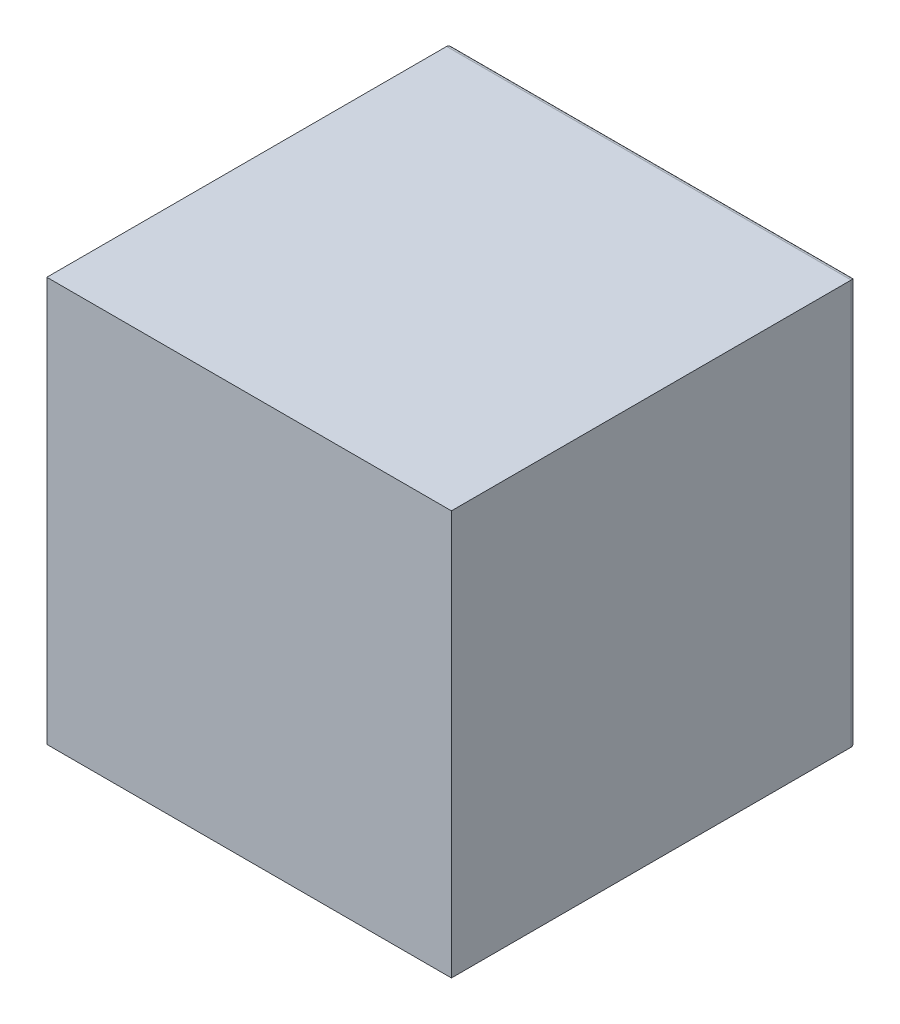
SolidWorks part; units mm, degrees
material "Stainless Steel (ferritic)"
ref_plane "Front Plane" through (0, 0, 0) normal (0, 0, 1) x (1, 0, 0)
ref_plane "Top Plane" through (0, 0, 0) normal (0, 1, 0) x (1, 0, 0)
ref_plane "Right Plane" through (0, 0, 0) normal (1, 0, 0) x (0, 0, -1)
sketch "Sketch2" plane through (0, 0, 0) normal (0, 1, 0) x (1, 0, 0)
  line L0 (250, -1250) -> (50250, -1250) construction
  line L1 (0, 0) -> (2500, 0)
  line L2 (0, 0) -> (0, -2500)
  line L3 (0, -2500) -> (2500, -2500)
  line L4 (2500, 0) -> (2500, -2500)
  line L5 (0, 0) -> (2500, -2500) construction
  line L6 (0, -2500) -> (2500, 0) construction
  line L7 (1250, -2250) -> (1250, 47750) construction
  point P4 (1250, -1250)
  dimension "D1" = 2500
  dimension "2500" = 2500
extrude "Boss-Extrude1" add sketch "Sketch2" along normal blind 2500
sketch "Sketch6" plane through (0, 0, 0) normal (0, 0, 1) x (1, 0, 0)
  line L0 (0, 250) -> (0, 50250) construction
  line L1 (0, 2500) -> (0, 0) construction
  line L2 (2500, 250) -> (2500, 50250) construction
  line L3 (2500, 2500) -> (2500, 0) construction
  line L4 (1500, 1250) -> (51500, 1250) construction
  line L6 (474.6639, 2000) -> (1974.6639, 2000)
  line L7 (474.6639, 2000) -> (474.6639, 500)
  line L8 (474.6639, 500) -> (1974.6639, 500)
  line L9 (1974.6639, 2000) -> (1974.6639, 500)
  line L10 (1224.6639, 500) -> (1224.6639, 2000) construction
  line L11 (474.6639, 1250) -> (1974.6639, 1250) construction
  point P5 (0, 1250)
  point P10 (2500, 1250)
  point P11 (1224.6639, 1250)
  dimension "D1" = 1500
  dimension "D2" = 1500
sketch "Sketch8" plane through (0, 0, 0) normal (0, 0, 1) x (1, 0, 0)
extrude "Cut-Extrude9" cut sketch "Sketch6" along normal blind 500
sketch "Sketch13" plane through (0, 0, 0) normal (0, 0, 1) x (1, 0, 0)
  line L1 (726.8707, 750) -> (1726.8707, 750)
  line L2 (726.8707, 750) -> (726.8707, 1750)
  line L3 (726.8707, 1750) -> (1726.8707, 1750)
  line L4 (1726.8707, 750) -> (1726.8707, 1750)
  line L5 (1226.8707, 1750) -> (1226.8707, 750) construction
  line L6 (726.8707, 1250) -> (1726.8707, 1250) construction
  point P0 (1226.8707, 1250)
  dimension "D1" = 1000
  dimension "D2" = 1000
fillet "Fillet2" radius 30 4 edges at (0, 1250, 0) (1250, 2500, 0) (2500, 1250, 0) (1250, 0, 0)
